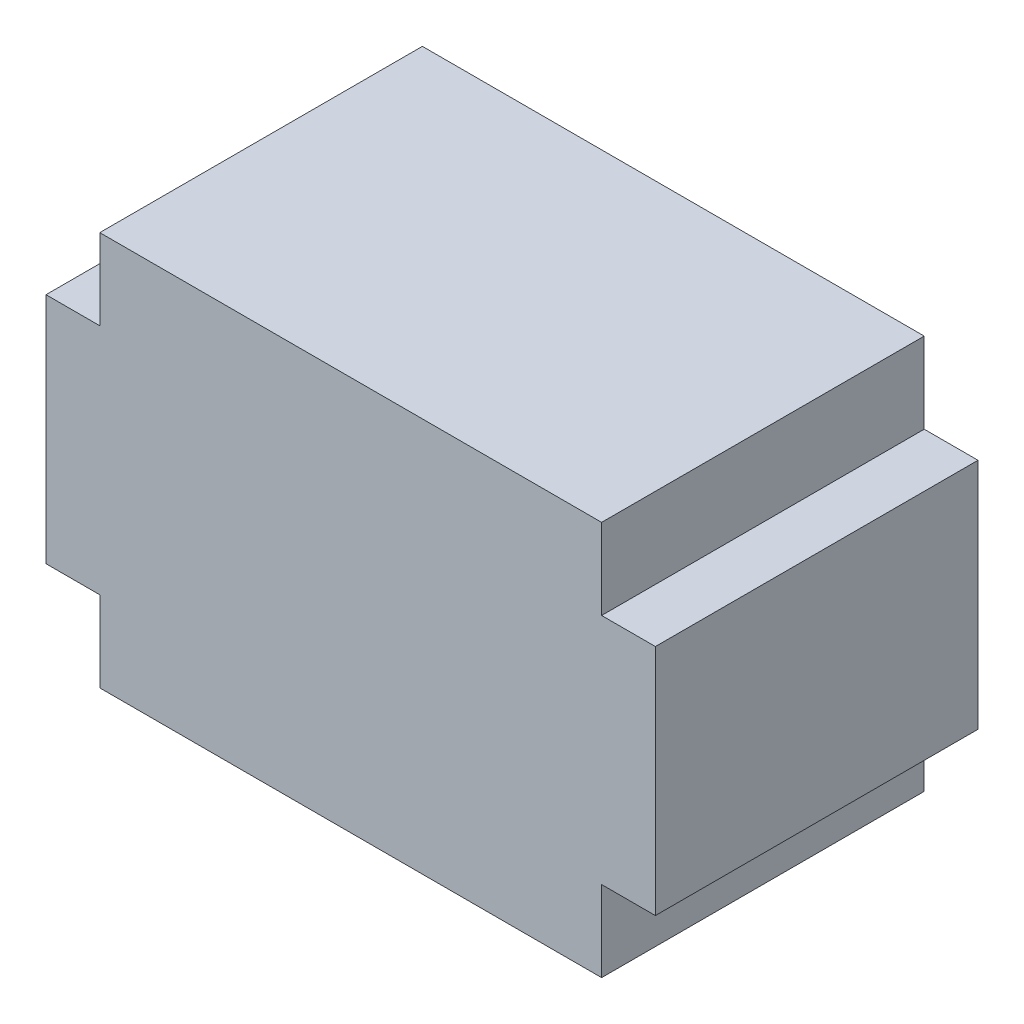
SolidWorks part; units mm, degrees
ref_plane "前视基准面" through (0, 0, 0) normal (0, 0, 1) x (1, 0, 0)
ref_plane "上视基准面" through (0, 0, 0) normal (0, 1, 0) x (1, 0, 0)
ref_plane "右视基准面" through (0, 0, 0) normal (1, 0, 0) x (0, 0, -1)
sketch "草图1" plane through (0, 0, 0) normal (0, 0, 1) x (1, 0, 0)
  line L0 (-1.4, -1.1) -> (-1.4, -0.65)
  line L1 (-1.4, -0.65) -> (-1.7, -0.65)
  line L2 (-1.7, -0.65) -> (-1.7, 0.65)
  line L3 (-1.7, 0.65) -> (-1.4, 0.65)
  line L4 (-1.4, 0.65) -> (-1.4, 1.1)
  line L5 (-1.4, 1.1) -> (1.4, 1.1)
  line L6 (1.4, 1.1) -> (1.4, 0.65)
  line L7 (1.4, 0.65) -> (1.7, 0.65)
  line L8 (1.7, 0.65) -> (1.7, -0.65)
  line L9 (1.7, -0.65) -> (1.4, -0.65)
  line L10 (1.4, -0.65) -> (1.4, -1.1)
  line L11 (1.4, -1.1) -> (-1.35, -1.1)
  line L12 (-1.35, -1.1) -> (-1.4, -1.1)
extrude "Component_Outline" add sketch "草图1" along normal blind 1.8 separate body
sketch3d "3D草图1"
  line L0 (0, 0, 0) -> (1, 0, 0)
  line L1 (0, 0, 0) -> (0, 1, 0)
  line L2 (0, 0, 0) -> (0, 0, 1)
  point P0 (0, 0, 0)
